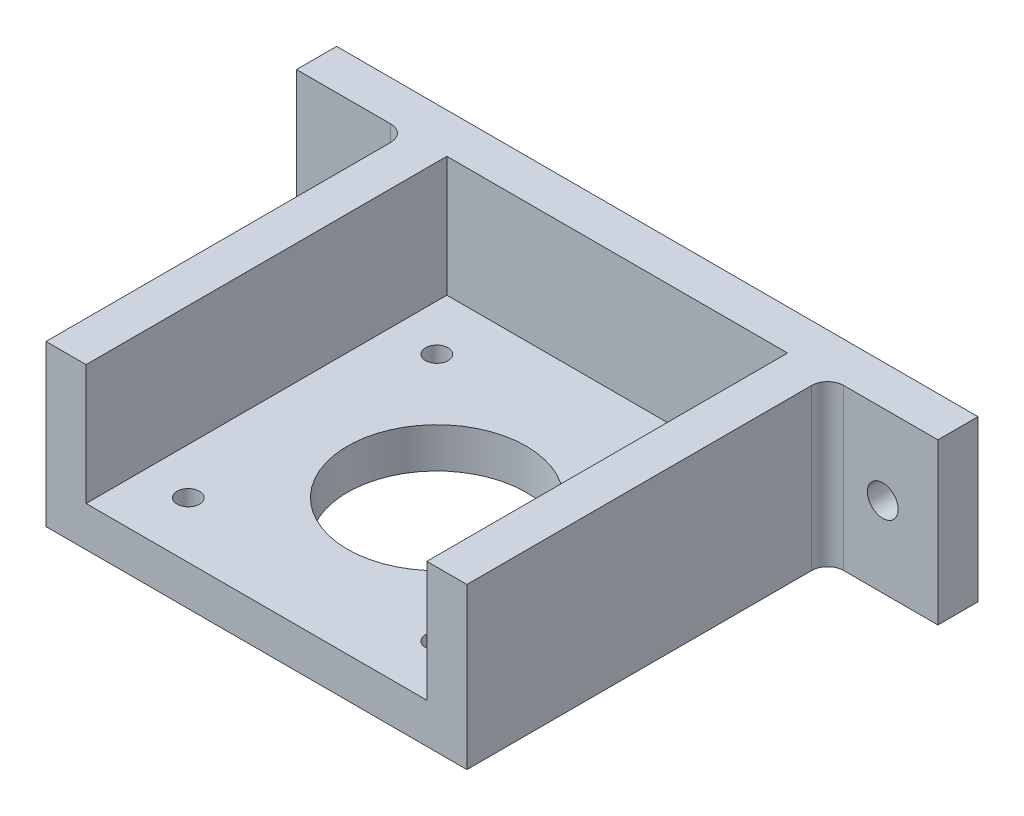
SolidWorks part; units mm, degrees
ref_plane "Front Plane" through (0, 0, 0) normal (0, 0, 1) x (1, 0, 0)
ref_plane "Top Plane" through (0, 0, 0) normal (0, 1, 0) x (1, 0, 0)
ref_plane "Right Plane" through (0, 0, 0) normal (1, 0, 0) x (0, 0, -1)
sketch "Sketch1" plane through (0, 0, 0) normal (0, 0, 1) x (1, 0, 0)
  line L0 (26.25, 0) -> (-26.25, 0)
  line L1 (-26.25, 0) -> (-26.25, 20)
  line L2 (-26.25, 20) -> (-21.25, 20)
  line L3 (-21.25, 20) -> (-21.25, 5)
  line L4 (-21.25, 5) -> (21.25, 5)
  line L5 (0, 0) -> (0, 15.5852) construction
  line L6 (26.25, 20) -> (21.25, 20)
  line L7 (21.25, 20) -> (21.25, 5)
  line L8 (26.25, 0) -> (26.25, 20)
  point P9 (0, 5)
  dimension "D1" = 5
  dimension "D2" = 42.5
  dimension "D3" = 5
  dimension "D4" = 20
extrude "Boss-Extrude1" add sketch "Sketch1" along normal blind 45
sketch "Sketch2" plane through (0, 0, 0) normal (1, 0, 0) x (0, 0, -1)
  line L0 (0, 0) -> (0, 20)
  line L1 (0, 20) -> (5, 20)
  line L2 (5, 20) -> (5, 0)
  line L3 (5, 0) -> (0, 0)
  line L4 (-45, 20) -> (0, 20) construction
  line L5 (-45, 0) -> (0, 0) construction
  dimension "D1" = 0
  dimension "D2" = 0
  dimension "D3" = 5
extrude "Boss-Extrude3" add sketch "Sketch2" along normal mid plane 80
sketch "Sketch3" plane through (0, 0, 0) normal (0, 0, 1) x (1, 0, 0)
  line L0 (-26.25, 0) -> (-40, 20) construction
  line L1 (-26.25, 20) -> (-40, 0) construction
  line L2 (0, 0) -> (0, 91.8291) construction
  circle A0 centre (-33.125, 10) radius 1.925
  circle A1 centre (33.125, 10) radius 1.925
  dimension "D1" = 3.85
extrude "Cut-Extrude1" cut sketch "Sketch3" against normal blind 200
sketch "Sketch4" plane through (0, 5, 0) normal (0, 1, 0) x (1, 0, 0)
  line L0 (-21.25, 0) -> (21.25, -45) construction
  line L1 (21.25, 0) -> (-21.25, -45) construction
  circle A0 centre (0, -22.5) radius 11.15
  dimension "D1" = 22.3
extrude "Cut-Extrude2" cut sketch "Sketch4" against normal blind 200
sketch "Sketch5" plane through (0, 5, 0) normal (0, 1, 0) x (1, 0, 0)
  line L0 (0, -22.5) -> (0, 0) construction
  line L1 (0, -22.5) -> (0, -12.0014) construction
  line L2 (-15.5, -7) -> (15.5, -7) construction
  line L3 (-15.5, -7) -> (-15.5, -38) construction
  line L4 (-15.5, -38) -> (15.5, -38) construction
  line L5 (15.5, -7) -> (15.5, -38) construction
  line L6 (-15.5, -7) -> (15.5, -38) construction
  line L7 (-15.5, -38) -> (15.5, -7) construction
  line L8 (0, -22.5) -> (-30.6648, -22.5) construction
  circle A0 centre (-15.5, -7) radius 1.4
  circle A1 centre (15.5, -7) radius 1.4
  circle A2 centre (-15.5, -38) radius 1.4
  circle A3 centre (15.5, -38) radius 1.4
  dimension "D3" = 2.8
  dimension "D1" = 31
  dimension "D2" = 31
extrude "Cut-Extrude3" cut sketch "Sketch5" against normal blind 200
fillet "Fillet1" radius 2 2 edges
